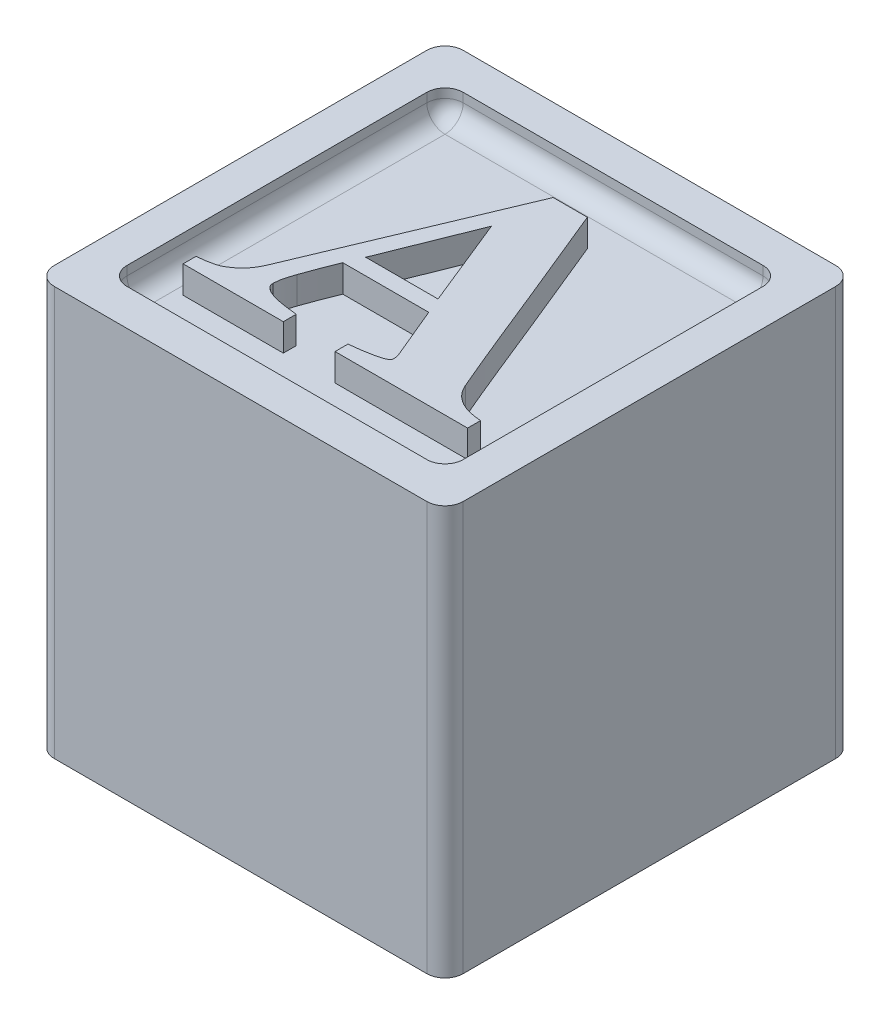
SolidWorks part; units mm, degrees
material "Maple"
ref_plane "Front" through (0, 0, 0) normal (0, 0, 1) x (1, 0, 0)
ref_plane "Top" through (0, 0, 0) normal (0, 1, 0) x (1, 0, 0)
ref_plane "Right" through (0, 0, 0) normal (1, 0, 0) x (0, 0, -1)
sketch "Sketch1" plane through (0, 0, 0) normal (0, 1, 0) x (1, 0, 0)
  line L1 (0, 0) -> (45, 0)
  line L2 (0, 0) -> (0, 45)
  line L3 (0, 45) -> (45, 45)
  line L4 (45, 0) -> (45, 45)
  dimension "D1" = 45
extrude "Boss-Extrude1" add sketch "Sketch1" along normal blind 45
sketch "Sketch2" plane through (0, 45, 0) normal (0, 1, 0) x (1, 0, 0)
  line L0 (0, 0) -> (4, 4) construction
  line L1 (6, 41) -> (39, 41)
  line L2 (4, 39) -> (4, 6)
  line L3 (6, 4) -> (39, 4)
  line L4 (41, 39) -> (41, 6)
  line L5 (41, 41) -> (45, 45) construction
  line L6 (0, 45) -> (0, 0) construction
  arc A0 (39, 41) -> (41, 39) centre (39, 39) cw
  arc A1 (39, 4) -> (41, 6) centre (39, 6) ccw
  arc A2 (4, 6) -> (6, 4) centre (6, 6) ccw
  arc A3 (6, 41) -> (4, 39) centre (6, 39) ccw
  dimension "D2" = 2
  dimension "D1" = 4
extrude "Cut-Extrude1" cut sketch "Sketch2" against normal blind 3
fillet "Fillet1" radius 2 8 edges at (41, 42, -22.5) (40.4142, 42, -4.5858) (22.5, 42, -4) (4.5858, 42, -4.5858) (4, 42, -22.5) (4.5858, 42, -40.4142) (22.5, 42, -41) (40.4142, 42, -40.4142)
sketch "Sketch3" plane through (0, 42, 0) normal (0, 1, 0) x (1, 0, 0)
  line L0 (8.0028, 9.2432) -> (36.562, 9.2432) construction
  text T0 "A" font "Georgia" height in points 100
extrude "Boss-Extrude2" add sketch "Sketch3" along normal blind 3
fillet "Fillet2" radius 2 3 edges at (45, 22.5, -45) (45, 22.5, 0) (0, 22.5, 0)
fillet "Fillet3" radius 2 1 edges at (0, 22.5, -45)
sketch3d "URDF Reference"
  line L0 (0, 0, 0) -> (10, 0, 0) construction
  line L1 (0, 0, 0) -> (0, 0, -10) construction
  point P0 (0, 0, 0)
